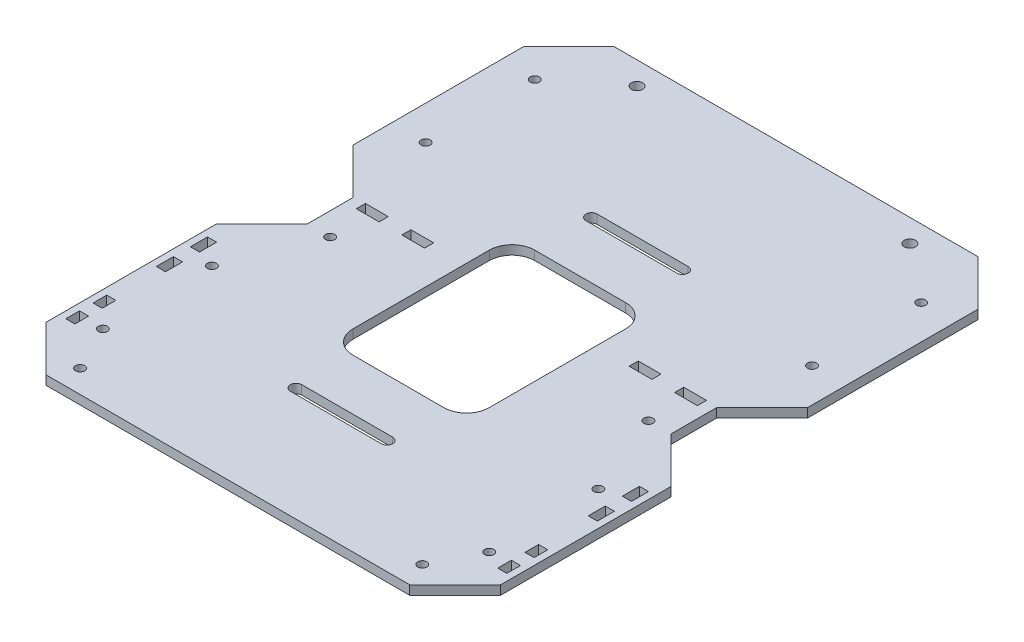
SolidWorks part; units mm, degrees
ref_plane "Front Plane" through (0, 0, 0) normal (0, 0, 1) x (1, 0, 0)
ref_plane "Top Plane" through (0, 0, 0) normal (0, 1, 0) x (1, 0, 0)
ref_plane "Right Plane" through (0, 0, 0) normal (1, 0, 0) x (0, 0, -1)
sketch "Sketch1" plane through (0, 0, 0) normal (0, 1, 0) x (1, 0, 0)
  line L0 (0, 14.4574) -> (0, 106.4081) construction
  line L1 (0, 126.5875) -> (0, 14.4574) construction
  line L2 (178.4753, -0.5426) -> (-178.4753, -0.5426) construction
  line L3 (80, 124.4574) -> (-80, 124.4574)
  line L4 (-100, 104.4574) -> (-100, 29.4574)
  line L5 (-100, 104.4574) -> (-80, 124.4574)
  line L6 (-80, -10.5426) -> (-80, 9.4574)
  line L7 (-80, 9.4574) -> (-100, 29.4574)
  line L8 (-20, 29.4574) -> (20, 29.4574)
  line L9 (30, 19.4574) -> (30, -40.5426)
  line L10 (20, -50.5426) -> (-20, -50.5426)
  line L11 (0, 106.4081) -> (0, 124.4574) construction
  line L12 (-30, -40.5426) -> (-30, 19.4574)
  line L13 (208.9496, -10.5426) -> (-198.9473, -10.5426) construction
  line L14 (30, -50.5426) -> (-30, -50.5426) construction
  line L15 (80, -10.5426) -> (80, 9.4574)
  line L16 (80, 9.4574) -> (100, 29.4574)
  line L17 (100, 104.4574) -> (80, 124.4574)
  line L18 (100, 104.4574) -> (100, 29.4574)
  line L19 (100, -105.5426) -> (100, -30.5426)
  line L20 (100, -105.5426) -> (80, -125.5426)
  line L21 (80, -10.5426) -> (100, -30.5426)
  line L22 (-80, -10.5426) -> (-100, -30.5426)
  line L23 (-100, -105.5426) -> (-80, -125.5426)
  line L24 (-100, -105.5426) -> (-100, -30.5426)
  line L25 (80, -125.5426) -> (-80, -125.5426)
  line L26 (30, 29.4574) -> (30, -50.5426) construction
  line L27 (-30, -50.5426) -> (-30, 29.4574) construction
  line L28 (-30, 29.4574) -> (30, 29.4574) construction
  line L29 (20, -75.5426) -> (-20, -75.5426) construction
  line L30 (20, -73.0426) -> (-20, -73.0426)
  line L31 (20, -78.0426) -> (-20, -78.0426)
  line L32 (0, -0.5426) -> (0, 14.4574) construction
  line L33 (-33.0964, 39.4574) -> (40, 39.4574) construction
  line L34 (0, -0.5426) -> (0, -127.6726) construction
  line L35 (40, 39.4574) -> (40, -60.5426) construction
  line L36 (40, -60.5426) -> (-40, -60.5426) construction
  line L37 (-40, -60.5426) -> (-40, 39.4574) construction
  line L38 (-40, 39.4574) -> (-33.0964, 39.4574) construction
  line L39 (-80, -75.1637) -> (80, -75.1637) construction
  line L40 (80, -75.1637) -> (80, -115.5426) construction
  line L41 (80, -115.5426) -> (-80, -115.5426) construction
  line L42 (-80, -115.5426) -> (-80, -75.1637) construction
  line L43 (128.2099, -71.5426) -> (-240.272, -71.5426) construction
  line L44 (97, -37.5) -> (97, -45)
  line L45 (97, -93.8222) -> (97, -99.8222)
  line L46 (75, 10) -> (65, 10)
  line L47 (93, -45) -> (93, -37.5)
  line L48 (97, -52.5) -> (97, -60)
  line L49 (97, -37.5) -> (93, -37.5)
  line L50 (97, -45) -> (93, -45)
  line L51 (97, -99.8222) -> (93, -99.8222)
  line L52 (93, -52.5) -> (97, -52.5)
  line L53 (97, -60) -> (93, -60)
  line L54 (93, -99.8222) -> (93, -93.8222)
  line L55 (93, -93.8222) -> (97, -93.8222)
  line L56 (55, 6) -> (45, 6)
  line L57 (97, -87.8222) -> (93, -87.8222)
  line L58 (93, -87.8222) -> (93, -81.8222)
  line L59 (93, -81.8222) -> (97, -81.8222)
  line L60 (93, -60) -> (93, -52.5)
  line L61 (97, -81.8222) -> (97, -87.8222)
  line L62 (-93, -99.8222) -> (-93, -93.8222)
  line L63 (-97, -99.8222) -> (-93, -99.8222)
  line L64 (-97, -93.8222) -> (-97, -99.8222)
  line L65 (-93, -93.8222) -> (-97, -93.8222)
  line L66 (-93, -87.8222) -> (-93, -81.8222)
  line L67 (-97, -87.8222) -> (-93, -87.8222)
  line L68 (-97, -81.8222) -> (-97, -87.8222)
  line L69 (-93, -81.8222) -> (-97, -81.8222)
  line L70 (-97, -60) -> (-93, -60)
  line L71 (-93, -60) -> (-93, -52.5)
  line L72 (-97, -52.5) -> (-97, -60)
  line L73 (-93, -52.5) -> (-97, -52.5)
  line L74 (-97, -45) -> (-93, -45)
  line L75 (-93, -45) -> (-93, -37.5)
  line L76 (-97, -37.5) -> (-93, -37.5)
  line L77 (-97, -37.5) -> (-97, -45)
  line L78 (-45, 6) -> (-55, 6)
  line L79 (75, 10) -> (75, 6)
  line L80 (65, 10) -> (65, 6)
  line L81 (55, 6) -> (55, 10)
  line L82 (45, 10) -> (45, 6)
  line L83 (55, 10) -> (45, 10)
  line L84 (-65, 6) -> (-75, 6)
  line L85 (-75, 10) -> (-75, 6)
  line L86 (-75, 10) -> (-65, 10)
  line L87 (-65, 10) -> (-65, 6)
  line L88 (-55, 6) -> (-55, 10)
  line L89 (-20, 19.4574) -> (20, 19.4574) construction
  line L90 (-45, 10) -> (-45, 6)
  line L91 (-55, 10) -> (-45, 10)
  line L92 (75, 6) -> (65, 6)
  line L93 (20, 19.4574) -> (20, -40.5426) construction
  line L94 (20, -40.5426) -> (-20, -40.5426) construction
  line L95 (-20, -40.5426) -> (-20, 19.4574) construction
  line L96 (-20, 19.4574) -> (-20, 19.4574) construction
  line L97 (20, 54.4574) -> (-20, 54.4574) construction
  line L98 (20, 51.9574) -> (-20, 51.9574)
  line L99 (20, 56.9574) -> (-20, 56.9574)
  line L100 (20, -75.1637) -> (-20, -75.1637) construction
  line L103 (-30, 29.4574) -> (-30, 29.4574) construction
  circle A0 centre (-85, 94.4574) radius 2
  circle A1 centre (-85, 46.4574) radius 2
  arc A2 (20, -50.5426) -> (30, -40.5426) centre (20, -40.5426) ccw
  arc A3 (-20, -50.5426) -> (-30, -40.5426) centre (-20, -40.5426) cw
  circle A4 centre (85, 94.4574) radius 2
  circle A5 centre (85, 46.4574) radius 2
  arc A6 (-30, 19.4574) -> (-20, 29.4574) centre (-20, 19.4574) cw
  arc A7 (20, 29.4574) -> (30, 19.4574) centre (20, 19.4574) cw
  circle A8 centre (85, -47.5426) radius 2
  circle A9 centre (85, -95.5426) radius 2
  circle A10 centre (-85, -47.5426) radius 2
  circle A11 centre (-85, -95.5426) radius 2
  arc A12 (20, -73.0426) -> (20, -78.0426) centre (20, -75.5426) cw
  arc A13 (-20, -78.0426) -> (-20, -73.0426) centre (-20, -75.5426) cw
  circle A14 centre (60, 114.4574) radius 2.5
  circle A15 centre (-60, 114.4574) radius 2.5
  circle A16 centre (-75, -115.5426) radius 2
  circle A17 centre (-70, -10.5426) radius 2
  circle A18 centre (75, -115) radius 2
  circle A19 centre (70, -10.5426) radius 2
  arc A20 (20, 51.9574) -> (20, 56.9574) centre (20, 54.4574) ccw
  arc A21 (-20, 56.9574) -> (-20, 51.9574) centre (-20, 54.4574) ccw
  point P6 (0, -0.5426)
  point P18 (-50, 69.4574)
  point P30 (50, 69.4574)
  point P53 (80, -0.5426)
  point P55 (-80, -0.5426)
  point P59 (50, -70.5426)
  point P66 (-50, -70.5426)
  point P68 (0, -75.5426)
  point P71 (0, 14.4574)
  point P82 (-30, 30)
  point P83 (30, 30)
  point P85 (30, -50)
  point P86 (-30, -50)
  point P94 (-30, 30)
  point P116 (95, -87.8222)
  point P153 (0, 54.4574)
  point P160 (0, -81.8222)
  point P161 (0, -75.1637)
  dimension "D8" = 4
  dimension "D9" = 4
  dimension "D22" = 4
  dimension "D24" = 5
  dimension "D26" = 10
  dimension "D39" = 10
  dimension "D13" = 10
  dimension "D1" = 100
  dimension "D2" = 125
  dimension "D5" = 15
  dimension "D6" = 30
  dimension "D7" = 48
  dimension "D10" = 20
  dimension "D11" = 10
  dimension "D12" = 10
  dimension "D14" = 15
  dimension "D15" = 80
  dimension "D16" = 60
  dimension "D17" = 40
  dimension "D18" = 20
  dimension "D19" = 160
  dimension "D20" = 30
  dimension "D21" = 24
  dimension "D23" = 10
  dimension "D25" = 5
  dimension "D27" = 10
  dimension "D28" = 3
  dimension "D29" = 5
  dimension "D30" = 20
  dimension "D31" = 7.5
  dimension "D32" = 7.5
  dimension "D33" = 7.5
  dimension "D34" = 6
  dimension "D35" = 6
  dimension "D36" = 6
  dimension "D37" = 10
  dimension "D38" = 10
  dimension "D40" = 4
  dimension "D41" = 60
extrude "Boss-Extrude1" add sketch "Sketch1" along normal blind 4
